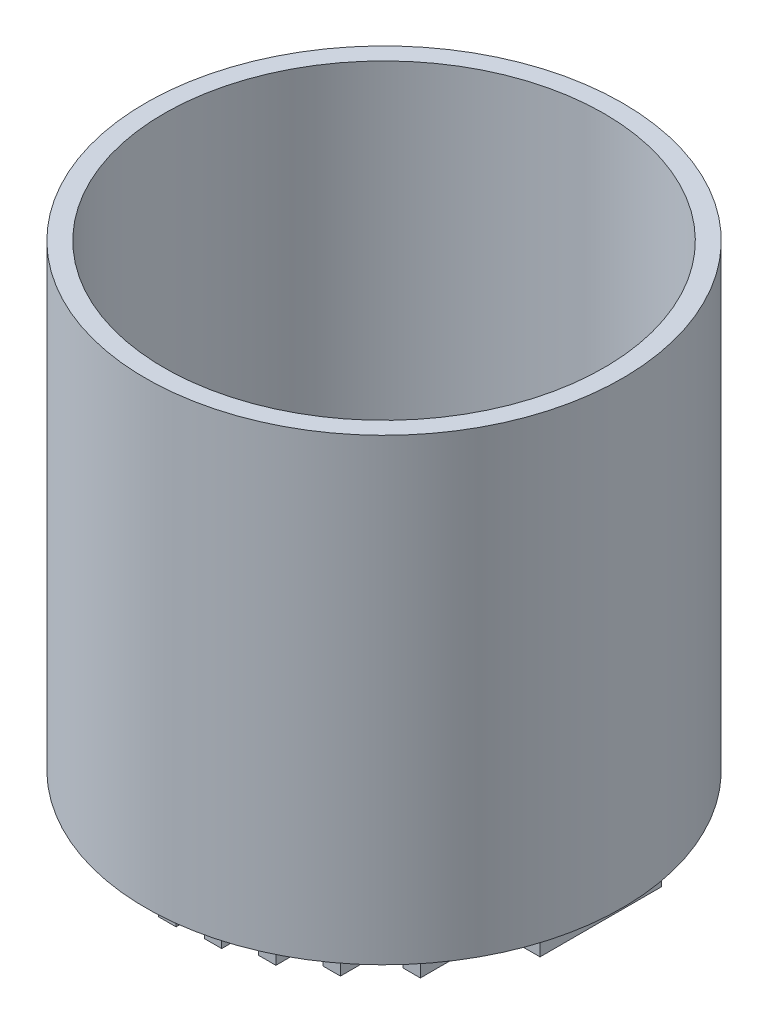
SolidWorks part; units mm, degrees
ref_plane "Front Plane" through (0, 0, 0) normal (0, 0, 1) x (1, 0, 0)
ref_plane "Top Plane" through (0, 0, 0) normal (0, 1, 0) x (1, 0, 0)
ref_plane "Right Plane" through (0, 0, 0) normal (1, 0, 0) x (0, 0, -1)
sketch "Sketch1" plane through (0, 0, 0) normal (0, 1, 0) x (1, 0, 0)
  circle A0 centre (0, 0) radius 38.1
  dimension "D1" = 76.2
extrude "Boss-Extrude1" add sketch "Sketch1" along normal blind 76.2
shell "Shell2" thickness 3.175
sketch "Sketch2" plane through (0, -3.175, 0) normal (0, -1, 0) x (1, 0, 0)
  line L0 (0, 0) -> (0, -37.5)
  line L1 (0, -37.5) -> (0, 37.5)
  line L4 (1.5, 37.5) -> (1.5, -37.5)
  line L5 (1.5, 37.5) -> (-1.5, 37.5)
  line L6 (1.5, -37.5) -> (-1.5, -37.5)
  line L7 (-1.5, 37.5) -> (-1.5, -37.5)
  line L8 (1.5, 37.5) -> (-1.5, -37.5) construction
  line L9 (1.5, -37.5) -> (-1.5, 37.5) construction
  line L10 (-1.5, 0) -> (-7.2, 0)
  line L11 (-5.7, 36.8023) -> (-5.7, -36.8023)
  line L12 (-5.7, 36.8023) -> (-8.7, 36.8023)
  line L13 (-5.7, -36.8023) -> (-8.7, -36.8023)
  line L14 (-8.7, 36.8023) -> (-8.7, -36.8023)
  line L15 (-5.7, 36.8023) -> (-8.7, -36.8023) construction
  line L16 (-5.7, -36.8023) -> (-8.7, 36.8023) construction
  line L17 (-7.2, 0) -> (-14.4, 0)
  line L18 (-12.9, 34.625) -> (-12.9, -34.625)
  line L19 (-12.9, 34.625) -> (-15.9, 34.625)
  line L20 (-12.9, -34.625) -> (-15.9, -34.625)
  line L21 (-15.9, 34.625) -> (-15.9, -34.625)
  line L22 (-12.9, 34.625) -> (-15.9, -34.625) construction
  line L23 (-12.9, -34.625) -> (-15.9, 34.625) construction
  line L24 (-14.4, 0) -> (-21.6, 0)
  line L25 (-20.1, 30.6544) -> (-20.1, -30.6544)
  line L26 (-20.1, 30.6544) -> (-23.1, 30.6544)
  line L27 (-20.1, -30.6544) -> (-23.1, -30.6544)
  line L28 (-23.1, 30.6544) -> (-23.1, -30.6544)
  line L29 (-20.1, 30.6544) -> (-23.1, -30.6544) construction
  line L30 (-20.1, -30.6544) -> (-23.1, 30.6544) construction
  line L31 (-21.6, 0) -> (-28.8, 0)
  line L32 (-27.3, 24.0169) -> (-27.3, -24.0169)
  line L33 (-27.3, 24.0169) -> (-30.3, 24.0169)
  line L34 (-27.3, -24.0169) -> (-30.3, -24.0169)
  line L35 (-30.3, 24.0169) -> (-30.3, -24.0169)
  line L36 (-27.3, 24.0169) -> (-30.3, -24.0169) construction
  line L37 (-27.3, -24.0169) -> (-30.3, 24.0169) construction
  line L38 (-28.8, 0) -> (-36, 0)
  line L39 (-34.5, 10.5) -> (-34.5, -10.5)
  line L40 (-34.5, 10.5) -> (-37.5, 10.5)
  line L41 (-34.5, -10.5) -> (-37.5, -10.5)
  line L42 (-37.5, 10.5) -> (-37.5, -10.5)
  line L43 (-34.5, 10.5) -> (-37.5, -10.5) construction
  line L44 (-34.5, -10.5) -> (-37.5, 10.5) construction
  line L45 (34.5, -10.5) -> (37.5, 10.5) construction
  line L46 (34.5, 10.5) -> (37.5, -10.5) construction
  line L47 (27.3, -24.0169) -> (30.3, 24.0169) construction
  line L48 (27.3, 24.0169) -> (30.3, -24.0169) construction
  line L49 (20.1, -30.6544) -> (23.1, 30.6544) construction
  line L50 (20.1, 30.6544) -> (23.1, -30.6544) construction
  line L51 (12.9, -34.625) -> (15.9, 34.625) construction
  line L52 (12.9, 34.625) -> (15.9, -34.625) construction
  line L53 (5.7, -36.8023) -> (8.7, 36.8023) construction
  line L54 (5.7, 36.8023) -> (8.7, -36.8023) construction
  line L55 (37.5, 10.5) -> (37.5, -10.5)
  line L56 (34.5, -10.5) -> (37.5, -10.5)
  line L57 (34.5, 10.5) -> (37.5, 10.5)
  line L58 (34.5, 10.5) -> (34.5, -10.5)
  line L59 (28.8, 0) -> (36, 0)
  line L60 (30.3, 24.0169) -> (30.3, -24.0169)
  line L61 (27.3, -24.0169) -> (30.3, -24.0169)
  line L62 (27.3, 24.0169) -> (30.3, 24.0169)
  line L63 (27.3, 24.0169) -> (27.3, -24.0169)
  line L64 (21.6, 0) -> (28.8, 0)
  line L65 (23.1, 30.6544) -> (23.1, -30.6544)
  line L66 (20.1, -30.6544) -> (23.1, -30.6544)
  line L67 (20.1, 30.6544) -> (23.1, 30.6544)
  line L68 (20.1, 30.6544) -> (20.1, -30.6544)
  line L69 (14.4, 0) -> (21.6, 0)
  line L70 (15.9, 34.625) -> (15.9, -34.625)
  line L71 (12.9, -34.625) -> (15.9, -34.625)
  line L72 (12.9, 34.625) -> (15.9, 34.625)
  line L73 (12.9, 34.625) -> (12.9, -34.625)
  line L74 (7.2, 0) -> (14.4, 0)
  line L75 (8.7, 36.8023) -> (8.7, -36.8023)
  line L76 (5.7, -36.8023) -> (8.7, -36.8023)
  line L77 (5.7, 36.8023) -> (8.7, 36.8023)
  line L78 (5.7, 36.8023) -> (5.7, -36.8023)
  point P62 (0, 0)
  point P63 (0, 0)
  dimension "D2" = 3
  dimension "D3" = 5.7
  dimension "D4" = 3
  dimension "D5" = 7.2
  dimension "D6" = 3
  dimension "D7" = 7.2
  dimension "D8" = 3
  dimension "D9" = 7.2
  dimension "D10" = 3
  dimension "D11" = 7.2
  dimension "D12" = 3
extrude "Boss-Extrude2" add sketch "Sketch2" along normal blind 4
